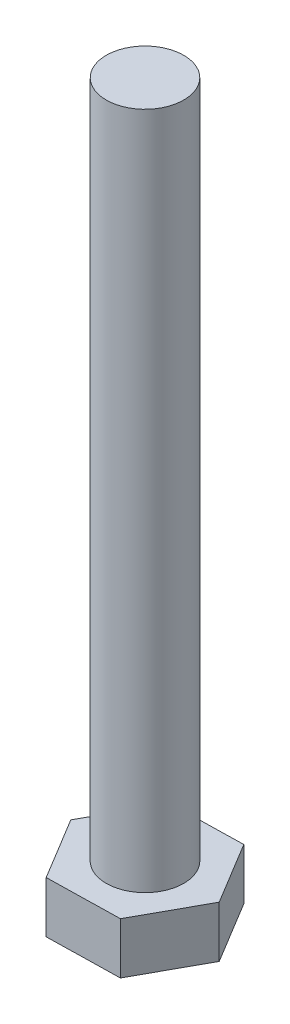
SolidWorks part; units mm, degrees
ref_plane "Front Plane" through (0, 0, 0) normal (0, 0, 1) x (1, 0, 0)
ref_plane "Top Plane" through (0, 0, 0) normal (0, 1, 0) x (1, 0, 0)
ref_plane "Right Plane" through (0, 0, 0) normal (1, 0, 0) x (0, 0, -1)
sketch "Sketch1" plane through (0, 0, 0) normal (0, 1, 0) x (1, 0, 0)
  line L1 (3.8835, -6.4227) -> (7.504, 0.1519)
  line L2 (7.504, 0.1519) -> (3.6205, 6.5746)
  line L3 (3.6205, 6.5746) -> (-3.8835, 6.4227)
  line L4 (-3.8835, 6.4227) -> (-7.504, -0.1519)
  line L5 (-7.504, -0.1519) -> (-3.6205, -6.5746)
  line L6 (-3.6205, -6.5746) -> (3.8835, -6.4227)
  circle A0 centre (0, 0) radius 6.5 construction
  dimension "D1" = 13
extrude "Boss-Extrude1" add sketch "Sketch1" along normal blind 5.3
sketch "Sketch2" plane through (0, 5.3, 0) normal (0, 1, 0) x (1, 0, 0)
  circle A0 centre (0, 0) radius 4
  dimension "D1" = 8
extrude "Boss-Extrude2" add sketch "Sketch2" along normal blind 70
